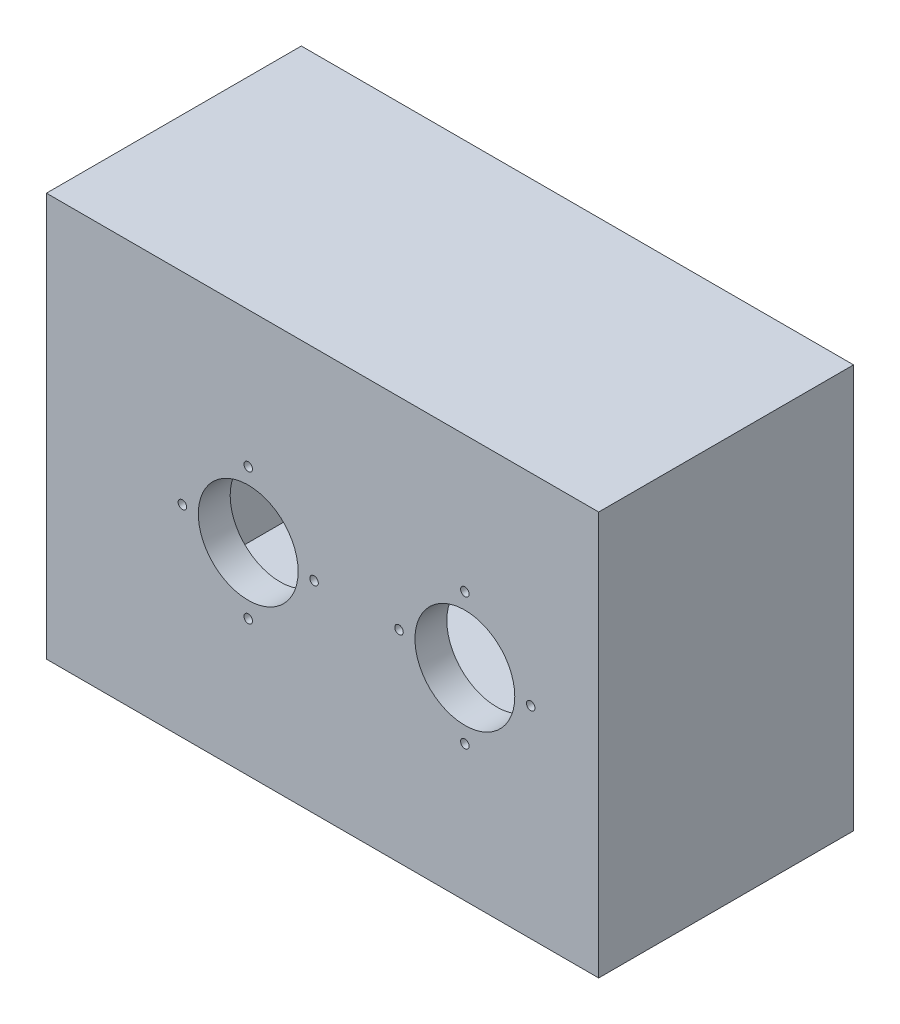
SolidWorks part; units mm, degrees
ref_plane "Front Plane" through (0, 0, 0) normal (0, 0, 1) x (1, 0, 0)
ref_plane "Top Plane" through (0, 0, 0) normal (0, 1, 0) x (1, 0, 0)
ref_plane "Right Plane" through (0, 0, 0) normal (1, 0, 0) x (0, 0, -1)
sketch "Sketch1" plane through (0, 0, 0) normal (0, 1, 0) x (1, 0, 0)
  line L1 (-130, 60) -> (130, 60)
  line L2 (-130, 60) -> (-130, -60)
  line L3 (-130, -60) -> (130, -60)
  line L4 (130, 60) -> (130, -60)
  line L5 (-130, 60) -> (130, -60) construction
  line L6 (-130, -60) -> (130, 60) construction
  point P0 (0, 0)
  dimension "D1" = 260
  dimension "D2" = 120
extrude "Boss-Extrude1" add sketch "Sketch1" along normal blind 190
shell "Shell1" thickness 15
sketch "Sketch2" plane through (0, 0, 60) normal (0, 0, 1) x (1, 0, 0)
  line L0 (-130, 190) -> (-130, 0) construction
  line L1 (-130, 190) -> (130, 190) construction
  circle A0 centre (-35, 95) radius 15
  circle A1 centre (67, 95) radius 15
  dimension "D1" = 30
  dimension "D2" = 30
  dimension "D3" = 95
  dimension "D4" = 102
  dimension "D5" = 95
  dimension "D6" = 95
extrude "Cut-Extrude1" cut sketch "Sketch2" against normal through all
sketch "Sketch3" plane through (0, 0, 60) normal (0, 0, 1) x (1, 0, 0)
  circle A0 centre (-35, 95) radius 23.5
  circle A1 centre (67, 95) radius 23.5
  dimension "D1" = 47
extrude "Cut-Extrude2" cut sketch "Sketch3" against normal through all contours A0 | A1
sketch "Sketch4" plane through (0, 0, 60) normal (0, 0, 1) x (1, 0, 0)
  line L1 (16, 95) -> (16, 134.681) construction
  circle A0 centre (-35, 126) radius 2
  circle A1 centre (-4, 95) radius 2
  circle A2 centre (-35, 64) radius 2
  circle A3 centre (-66, 95) radius 2
  circle A8 centre (98, 95) radius 2
  circle A9 centre (67, 64) radius 2
  circle A10 centre (36, 95) radius 2
  circle A11 centre (67, 126) radius 2
  point P13 (-35, 95)
  point P22 (67, 95)
  dimension "D1" = 4
  dimension "D2" = 31
extrude "Cut-Extrude3" cut sketch "Sketch4" against normal through all contours A10 | A11 | A8 | A9 | A1 | A2 | A3 | A0
